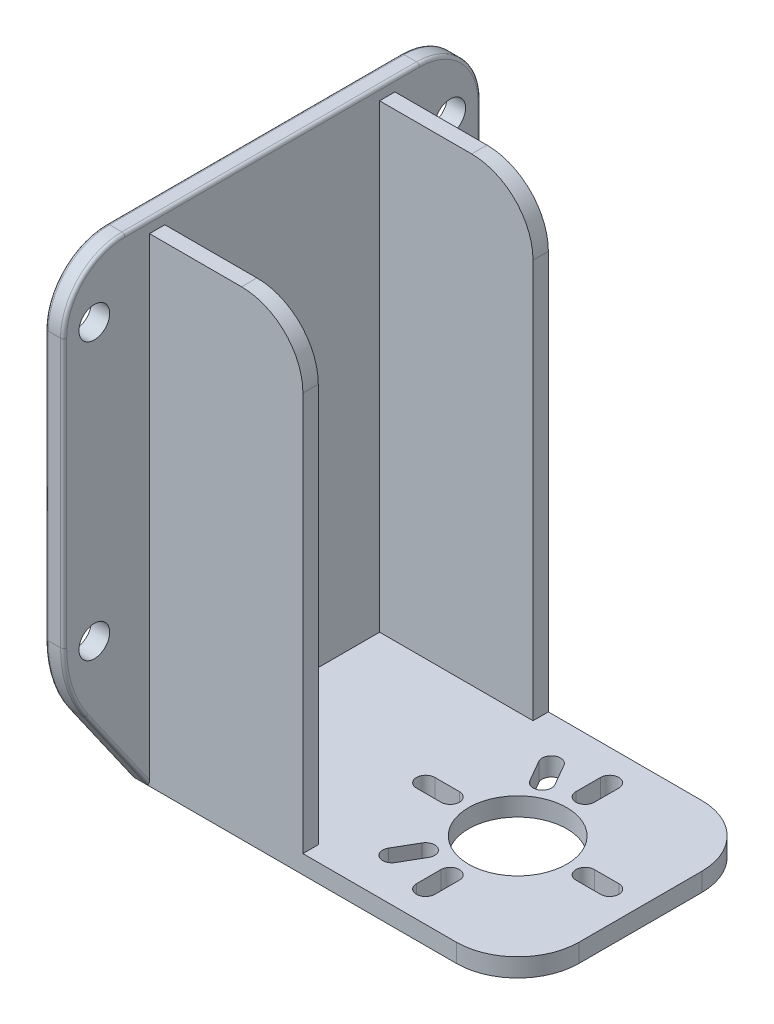
SolidWorks part; units mm, degrees
ref_plane "前视基准面" through (0, 0, 0) normal (0, 0, 1) x (1, 0, 0)
ref_plane "上视基准面" through (0, 0, 0) normal (0, 1, 0) x (1, 0, 0)
ref_plane "右视基准面" through (0, 0, 0) normal (1, 0, 0) x (0, 0, -1)
sketch "草图1" plane through (0, 0, 0) normal (0, 1, 0) x (1, 0, 0)
  line L0 (-53.6479, 53.1266) -> (-53.6479, 13.1266) construction
  line L1 (-73.6479, 53.1266) -> (-13.6479, 53.1266)
  line L2 (-73.6479, 53.1266) -> (-73.6479, 13.1266)
  line L3 (-73.6479, 13.1266) -> (-13.6479, 13.1266)
  line L4 (-13.6479, 53.1266) -> (-13.6479, 13.1266)
  line L5 (-18.6479, 33.1266) -> (-22.6479, 33.1266) construction
  line L6 (-18.6479, 31.6266) -> (-22.6479, 31.6266)
  line L7 (-18.6479, 34.6266) -> (-22.6479, 34.6266)
  line L8 (-33.6479, 18.1266) -> (-33.6479, 22.1266) construction
  line L9 (-35.1479, 18.1266) -> (-35.1479, 22.1266)
  line L10 (-32.1479, 18.1266) -> (-32.1479, 22.1266)
  line L11 (-48.6479, 33.1266) -> (-44.6479, 33.1266) construction
  line L12 (-48.6479, 34.6266) -> (-44.6479, 34.6266)
  line L13 (-48.6479, 31.6266) -> (-44.6479, 31.6266)
  line L14 (-33.6479, 48.1266) -> (-33.6479, 44.1266) construction
  line L15 (-32.1479, 48.1266) -> (-32.1479, 44.1266)
  line L16 (-35.1479, 48.1266) -> (-35.1479, 44.1266)
  line L17 (-41.1479, 20.1362) -> (-39.1479, 23.6003) construction
  line L18 (-42.447, 20.8862) -> (-40.447, 24.3503)
  line L19 (-39.8489, 19.3862) -> (-37.8489, 22.8503)
  line L20 (-41.1479, 46.117) -> (-39.1479, 42.6529) construction
  line L21 (-39.8489, 46.867) -> (-37.8489, 43.4029)
  line L22 (-42.447, 45.367) -> (-40.447, 41.9029)
  circle A0 centre (-33.6479, 33.1266) radius 8
  arc A1 (-35.1479, 18.1266) -> (-32.1479, 18.1266) centre (-33.6479, 18.1266) ccw
  arc A2 (-18.6479, 31.6266) -> (-18.6479, 34.6266) centre (-18.6479, 33.1266) ccw
  arc A3 (-22.6479, 34.6266) -> (-22.6479, 31.6266) centre (-22.6479, 33.1266) ccw
  arc A4 (-32.1479, 22.1266) -> (-35.1479, 22.1266) centre (-33.6479, 22.1266) ccw
  arc A5 (-48.6479, 34.6266) -> (-48.6479, 31.6266) centre (-48.6479, 33.1266) ccw
  arc A6 (-44.6479, 31.6266) -> (-44.6479, 34.6266) centre (-44.6479, 33.1266) ccw
  arc A7 (-32.1479, 48.1266) -> (-35.1479, 48.1266) centre (-33.6479, 48.1266) ccw
  arc A8 (-35.1479, 44.1266) -> (-32.1479, 44.1266) centre (-33.6479, 44.1266) ccw
  arc A9 (-42.447, 20.8862) -> (-39.8489, 19.3862) centre (-41.1479, 20.1362) ccw
  arc A10 (-37.8489, 22.8503) -> (-40.447, 24.3503) centre (-39.1479, 23.6003) ccw
  arc A11 (-39.8489, 46.867) -> (-42.447, 45.367) centre (-41.1479, 46.117) ccw
  arc A12 (-40.447, 41.9029) -> (-37.8489, 43.4029) centre (-39.1479, 42.6529) ccw
  point P12 (-20.6479, 33.1266)
  point P20 (-33.6479, 20.1266)
  point P27 (-46.6479, 33.1266)
  point P34 (-33.6479, 46.1266)
  point P39 (-33.6479, 33.1266)
  point P41 (-40.1479, 21.8683)
  point P48 (-40.1479, 44.3849)
  point P53 (-33.6479, 33.1266)
  dimension "D2" = 16
  dimension "D3" = 20
  dimension "D1" = 60
  dimension "D4" = 4
  dimension "D6" = 40
  dimension "D7" = 40
  dimension "D5" = 11
  dimension "D8" = 3
  dimension "D9" = 4
  dimension "D10" = 3
extrude "凸台-拉伸1" add sketch "草图1" along normal blind 3
sketch "草图2" plane through (-73.6479, 0, 0) normal (-1, 0, 0) x (0, 0, 1)
  line L0 (-67.1307, 20) -> (-53.1266, 0)
  line L1 (-67.1307, 20) -> (0.8776, 20)
  line L2 (-53.1266, 0) -> (-13.1266, 0)
  line L3 (0.8776, 20) -> (-13.1266, 0)
  line L4 (-53.1266, 0) -> (-13.1266, 0) construction
  dimension "D1" = 20
  dimension "D2" = 55
  dimension "D3" = 55
  dimension "D4" = 68.0083
extrude "凸台-拉伸2" add sketch "草图2" along normal blind 3
sketch "草图6" plane through (0, 20, 0) normal (0, 1, 0) x (1, 0, 0)
  line L1 (-73.6479, 67.1307) -> (-76.6479, 67.1307)
  line L2 (-73.6479, 67.1307) -> (-73.6479, -0.8776)
  line L3 (-73.6479, -0.8776) -> (-76.6479, -0.8776)
  line L4 (-76.6479, 67.1307) -> (-76.6479, -0.8776)
extrude "凸台-拉伸3" add sketch "草图6" along normal blind 60
sketch "草图7" plane through (-73.6479, 0, 0) normal (1, 0, 0) x (0, 0, -1)
  line L0 (67.1307, 80) -> (67.1307, 20) construction
  line L1 (-0.8776, 80) -> (-0.8776, 20) construction
  line L2 (-0.8776, 80) -> (67.1307, 80) construction
  circle A0 centre (62.1307, 25) radius 2.5
  circle A1 centre (4.1307, 25) radius 2.5
  circle A2 centre (62.1307, 70) radius 2.5
  circle A3 centre (4.1307, 70) radius 2.5
  dimension "D1" = 5
  dimension "D3" = 58
  dimension "D4" = 5
  dimension "D5" = 5.0083
  dimension "D6" = 45
  dimension "D7" = 10
extrude "切除-拉伸1" cut sketch "草图7" against normal through all
fillet "圆角1" radius 10 2 edges at (-13.6479, 1.5, -13.1266) (-13.6479, 1.5, -53.1266)
fillet "圆角2" radius 20 2 edges at (-75.1479, 20, -67.1307) (-75.1479, 20, 0.8776)
fillet "圆角4" radius 10 2 edges at (-75.1479, 80, 0.8776) (-75.1479, 80, -67.1307)
sketch "草图8" plane through (0, 0, -53.1266) normal (0, 0, -1) x (-1, 0, 0)
  line L0 (73.6479, 3) -> (63.6479, 3)
  line L1 (23.6479, 3) -> (73.6479, 3) construction
  line L2 (63.6479, 3) -> (73.6479, 13)
  line L3 (73.6479, 13) -> (73.6479, 3)
  dimension "D1" = 10
  dimension "D2" = 10
extrude "凸台-拉伸4" [suppressed] add sketch "草图8" against normal blind 3
sketch "草图9" plane through (0, 0, -13.1266) normal (0, 0, 1) x (1, 0, 0)
  line L0 (-73.6479, 3) -> (-63.6479, 3)
  line L1 (-73.6479, 3) -> (-23.6479, 3) construction
  line L2 (-63.6479, 3) -> (-73.6479, 13)
  line L3 (-73.6479, 13) -> (-73.6479, 3)
  dimension "D1" = 10
  dimension "D2" = 10
extrude "凸台-拉伸5" [suppressed] add sketch "草图9" against normal blind 3
fillet "圆角5" [suppressed] radius 0.5
fillet "圆角12" radius 0.5 9 edges at (-73.6479, 7.4172, -58.3202) (-73.6479, 20.2919, -66.2051) (-73.6479, 48.153, -67.1307) (-73.6479, 77.0711, -64.2018) (-73.6479, 80, -33.1266) (-73.6479, 77.0711, -2.0514) (-73.6479, 7.4172, -7.933) (-73.6479, 20.2919, -0.0481) (-73.6479, 48.153, 0.8776)
fillet "圆角13" radius 0.5 9 edges at (-76.6479, 7.4172, -58.3202) (-76.6479, 20.2919, -66.2051) (-76.6479, 48.153, -67.1307) (-76.6479, 77.0711, -64.2018) (-76.6479, 80, -33.1266) (-76.6479, 77.0711, -2.0514) (-76.6479, 7.4172, -7.933) (-76.6479, 20.2919, -0.0481) (-76.6479, 48.153, 0.8776)
fillet "圆角14" [suppressed] radius 0.5
fillet "圆角15" [suppressed] radius 0.5
sketch "草图10" plane through (0, 3, 0) normal (0, 1, 0) x (1, 0, 0)
  line L1 (-73.6479, 53.1266) -> (-48.6479, 53.1266)
  line L2 (-73.6479, 53.1266) -> (-73.6479, 50.6266)
  line L3 (-73.6479, 50.6266) -> (-48.6479, 50.6266)
  line L4 (-48.6479, 53.1266) -> (-48.6479, 50.6266)
  line L5 (-73.6479, 13.1266) -> (-48.6479, 13.1266)
  line L6 (-73.6479, 13.1266) -> (-73.6479, 15.6266)
  line L7 (-73.6479, 15.6266) -> (-48.6479, 15.6266)
  line L8 (-48.6479, 13.1266) -> (-48.6479, 15.6266)
  dimension "D1" = 25
  dimension "D2" = 2.5
extrude "凸台-拉伸6" add sketch "草图10" along normal blind 75
fillet "圆角16" radius 10 2 edges at (-48.6479, 78, -14.3766) (-48.6479, 78, -51.8766)
